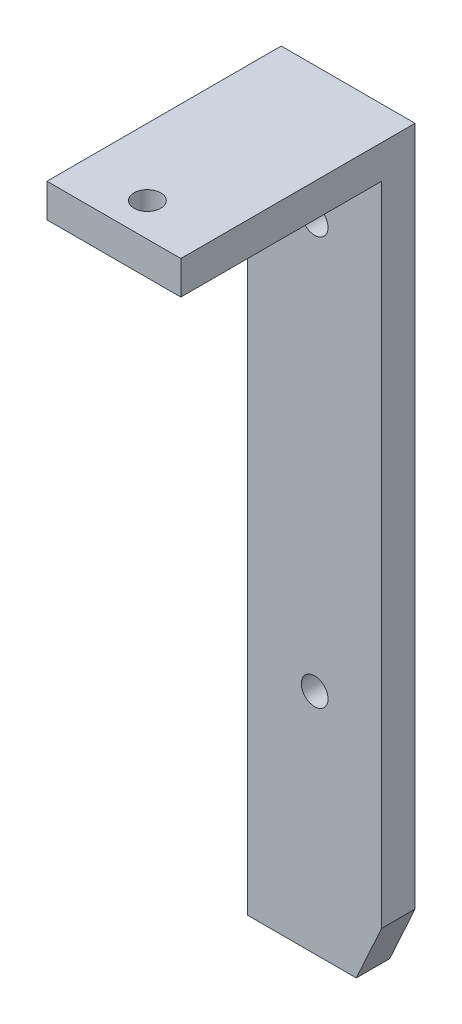
SolidWorks part; units mm, degrees
ref_plane "Front Plane" through (0, 0, 0) normal (0, 0, 1) x (1, 0, 0)
ref_plane "Top Plane" through (0, 0, 0) normal (0, 1, 0) x (1, 0, 0)
ref_plane "Right Plane" through (0, 0, 0) normal (1, 0, 0) x (0, 0, -1)
sketch "Sketch1" plane through (0, 0, 0) normal (0, 1, 0) x (1, 0, 0)
  line L1 (6.35, -1.5875) -> (-6.35, -1.5875)
  line L2 (6.35, -1.5875) -> (6.35, 1.5875)
  line L3 (6.35, 1.5875) -> (-6.35, 1.5875)
  line L4 (-6.35, -1.5875) -> (-6.35, 1.5875)
  line L5 (6.35, -1.5875) -> (-6.35, 1.5875) construction
  line L6 (6.35, 1.5875) -> (-6.35, -1.5875) construction
  point P0 (0, 0)
  dimension "D1" = 3.175
  dimension "D2" = 12.7
extrude "Boss-Extrude1" add sketch "Sketch1" along normal blind 69.85
sketch "Sketch2" plane through (0, 0, 1.5875) normal (0, 0, 1) x (1, 0, 0)
  line L0 (6.35, 69.85) -> (6.35, 0) construction
  line L1 (-6.35, 69.85) -> (6.35, 69.85)
  line L2 (-6.35, 69.85) -> (-6.35, 66.675)
  line L3 (-6.35, 66.675) -> (6.35, 66.675)
  line L4 (6.35, 69.85) -> (6.35, 66.675)
  dimension "D1" = 3.175
extrude "Boss-Extrude2" add sketch "Sketch2" along normal blind 19.05
sketch "Sketch3" plane through (0, 66.675, 0) normal (0, -1, 0) x (1, 0, 0)
  line L0 (0, 20.6375) -> (0, -1.5875) construction
  line L1 (-6.35, 20.6375) -> (6.35, 20.6375) construction
  line L2 (6.35, -1.5875) -> (-6.35, -1.5875) construction
  circle A0 centre (0, 17.4625) radius 1.27
  dimension "D1" = 2.54
  dimension "D2" = 19.05
extrude "Cut-Extrude1" cut sketch "Sketch3" against normal through all
sketch "Sketch4" plane through (0, 0, 1.5875) normal (0, 0, 1) x (1, 0, 0)
  line L0 (0, 66.675) -> (0, 0) construction
  line L1 (-6.35, 66.675) -> (6.35, 66.675) construction
  line L2 (-6.35, 0) -> (6.35, 0) construction
  circle A0 centre (0, 21.59) radius 1.27
  circle A1 centre (0, 60.325) radius 1.27
  dimension "D1" = 2.54
  dimension "D3" = 2.54
  dimension "D2" = 21.59
  dimension "D4" = 6.35
extrude "Cut-Extrude2" cut sketch "Sketch4" against normal through all
sketch "Sketch5" plane through (0, 0, -1.5875) normal (0, 0, -1) x (-1, 0, 0)
  circle A0 centre (0, 21.59) radius 1.27 construction
  circle A1 centre (0, 21.59) radius 1.27
  circle A2 centre (0, 21.59) radius 6.35
  dimension "D1" = 12.7
extrude "Boss-Extrude3" [suppressed] add sketch "Sketch5" along normal blind 10.16
sketch "Sketch6" plane through (0, 0, 1.5875) normal (0, 0, 1) x (1, 0, 0)
  line L0 (3.9515, 0) -> (6.35, 5.2717)
  line L1 (-6.35, 0) -> (6.35, 0) construction
  line L2 (6.35, 66.675) -> (6.35, 0) construction
  line L3 (6.35, 5.2717) -> (6.35, 0)
  line L4 (6.35, 0) -> (3.9515, 0)
extrude "Cut-Extrude3" cut sketch "Sketch6" against normal through all
